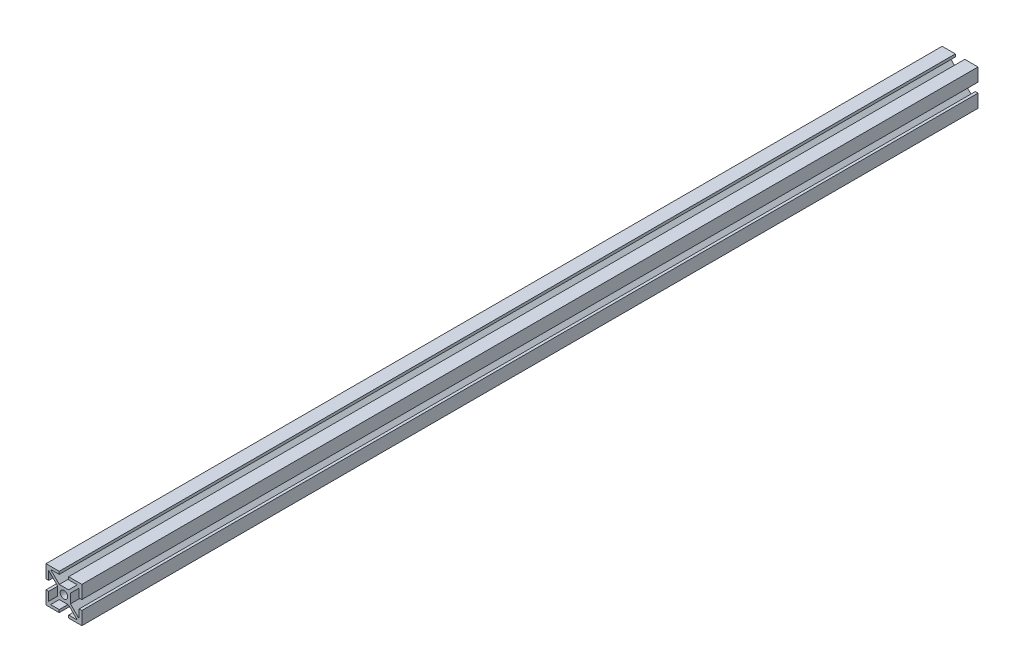
SolidWorks part; units mm, degrees
material "6063-T5"
ref_plane "Front Plane" through (0, 0, 0) normal (0, 0, 1) x (1, 0, 0)
ref_plane "Top Plane" through (0, 0, 0) normal (0, 1, 0) x (1, 0, 0)
ref_plane "Right Plane" through (0, 0, 0) normal (1, 0, 0) x (0, 0, -1)
sketch "Sketch1" plane through (0, 0, 0) normal (0, 0, 1) x (1, 0, 0)
  line L0 (0, 20) -> (20, 0) construction
  line L1 (0, 0) -> (20, 0) construction
  line L2 (0, 0) -> (0, 20) construction
  line L3 (0, 20) -> (20, 20) construction
  line L4 (20, 0) -> (20, 20) construction
  line L5 (20, 20) -> (0, 0) construction
  line L6 (18.5, 1.5) -> (18.5, 0) construction
  line L7 (1.5, 1.5) -> (18.5, 1.5) construction
  line L8 (1.5, 1.5) -> (1.5, 18.5) construction
  line L9 (1.5, 18.5) -> (18.5, 18.5) construction
  line L10 (18.5, 1.5) -> (18.5, 18.5) construction
  line L11 (18.5, 1.5) -> (20, 1.5) construction
  line L12 (6.345, 12.5943) -> (1.5, 17.4393)
  line L13 (13.655, 6.345) -> (6.345, 6.345) construction
  line L14 (13.655, 6.345) -> (13.655, 13.655) construction
  line L15 (13.655, 13.655) -> (6.345, 13.655) construction
  line L16 (6.345, 6.345) -> (6.345, 13.655) construction
  line L17 (7.4057, 13.655) -> (2.5607, 18.5)
  line L18 (2.5607, 18.5) -> (2.0303, 17.9697) construction
  line L19 (2.0303, 17.9697) -> (1.5, 17.4393) construction
  line L20 (6.345, 7.4057) -> (6.345, 12.5943)
  line L21 (12.5943, 13.655) -> (17.4393, 18.5)
  line L22 (17.4393, 18.5) -> (17.9697, 17.9697) construction
  line L23 (17.9697, 17.9697) -> (18.5, 17.4393) construction
  line L24 (18.5, 17.4393) -> (13.655, 12.5943)
  line L25 (13.655, 7.4057) -> (18.5, 2.5607)
  line L26 (18.5, 2.5607) -> (17.9697, 2.0303) construction
  line L27 (17.4393, 1.5) -> (12.5943, 6.345)
  line L28 (7.4057, 6.345) -> (2.5607, 1.5)
  line L29 (17.9697, 2.0303) -> (17.4393, 1.5) construction
  line L30 (1.5, 2.5607) -> (6.345, 7.4057)
  line L31 (2.5607, 1.5) -> (2.0303, 2.0303) construction
  line L32 (2.0303, 2.0303) -> (1.5, 2.5607) construction
  line L33 (7.4057, 13.655) -> (12.5943, 13.655)
  line L34 (13.655, 12.5943) -> (13.655, 7.4057)
  line L36 (12.5943, 6.345) -> (7.4057, 6.345)
  line L37 (0, 10) -> (1.5, 10) construction
  line L38 (0.75, 12.63) -> (0.75, 10) construction
  line L39 (0.75, 10) -> (0.75, 7.37) construction
  line L40 (1.5, 12.63) -> (0, 12.63)
  line L41 (1.5, 7.37) -> (0, 7.37)
  line L42 (10, 1.5) -> (10, 0) construction
  line L43 (10, 0.75) -> (12.63, 0.75) construction
  line L44 (10, 0.75) -> (7.37, 0.75) construction
  line L45 (12.63, 0) -> (12.63, 1.5)
  line L46 (7.37, 1.5) -> (7.37, 0)
  line L47 (18.5, 12.63) -> (20, 12.63)
  line L48 (18.5, 7.37) -> (20, 7.37)
  line L49 (7.37, 20) -> (7.37, 18.5)
  line L50 (12.63, 20) -> (12.63, 18.5)
  line L51 (2.5607, 1.5) -> (7.37, 1.5)
  line L52 (12.63, 1.5) -> (17.4393, 1.5)
  line L53 (18.5, 7.37) -> (18.5, 2.5607)
  line L54 (18.5, 12.63) -> (18.5, 17.4393)
  line L55 (17.4393, 18.5) -> (12.63, 18.5)
  line L56 (7.37, 18.5) -> (2.5607, 18.5)
  line L57 (1.5, 17.4393) -> (1.5, 12.63)
  line L58 (1.5, 7.37) -> (1.5, 2.5607)
  line L59 (7.37, 0) -> (0, 0)
  line L60 (0, 0) -> (0, 7.37)
  line L61 (0, 12.63) -> (0, 20)
  line L62 (0, 20) -> (7.37, 20)
  line L63 (12.63, 20) -> (20, 20)
  line L64 (20, 20) -> (20, 12.63)
  line L65 (20, 7.37) -> (20, 0)
  line L66 (20, 0) -> (12.63, 0)
  circle A0 centre (10, 10) radius 2.095
  dimension "D2" = 4.19
  dimension "D6" = 5.26
  dimension "D1" = 20
  dimension "D3" = 1.5
  dimension "D4" = 3.655
  dimension "D5" = 1.5
extrude "Boss-Extrude1" add sketch "Sketch1" along normal blind 500
